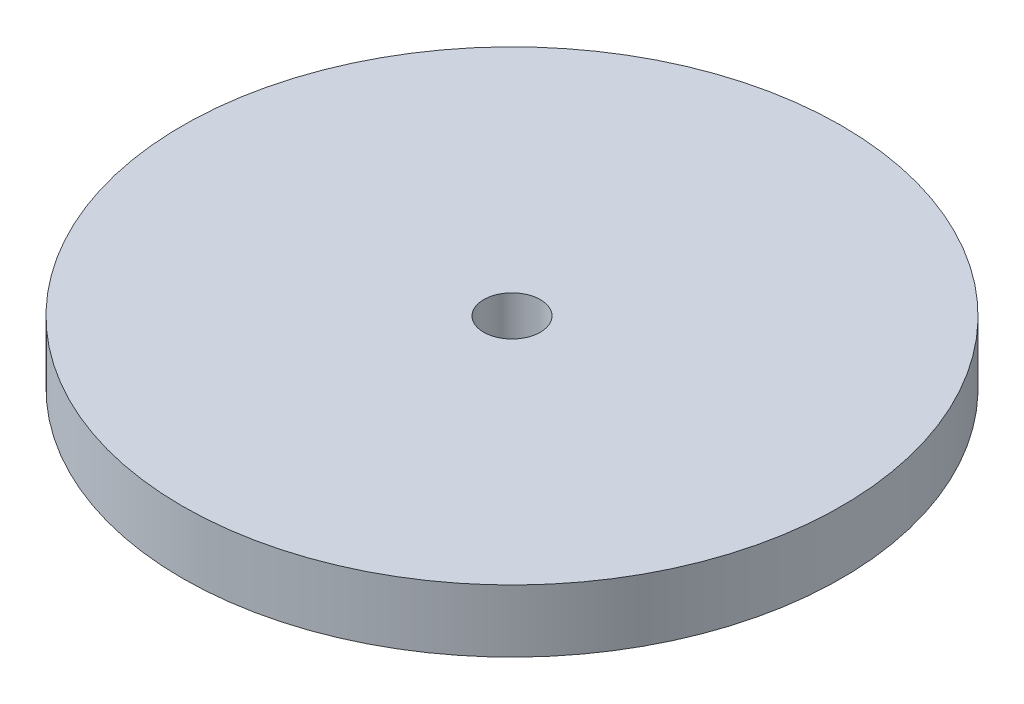
SolidWorks part; units mm, degrees
ref_plane "Front Plane" through (0, 0, 0) normal (0, 0, 1) x (1, 0, 0)
ref_plane "Top Plane" through (0, 0, 0) normal (0, 1, 0) x (1, 0, 0)
ref_plane "Right Plane" through (0, 0, 0) normal (1, 0, 0) x (0, 0, -1)
sketch "Sketch1" plane through (0, 0, 0) normal (0, 1, 0) x (1, 0, 0)
  circle A0 centre (0, 0) radius 337.5
  circle A1 centre (0, 0) radius 29
  dimension "D1" = 675
  dimension "D2" = 58
extrude "Boss-Extrude1" add sketch "Sketch1" along normal mid plane 64
